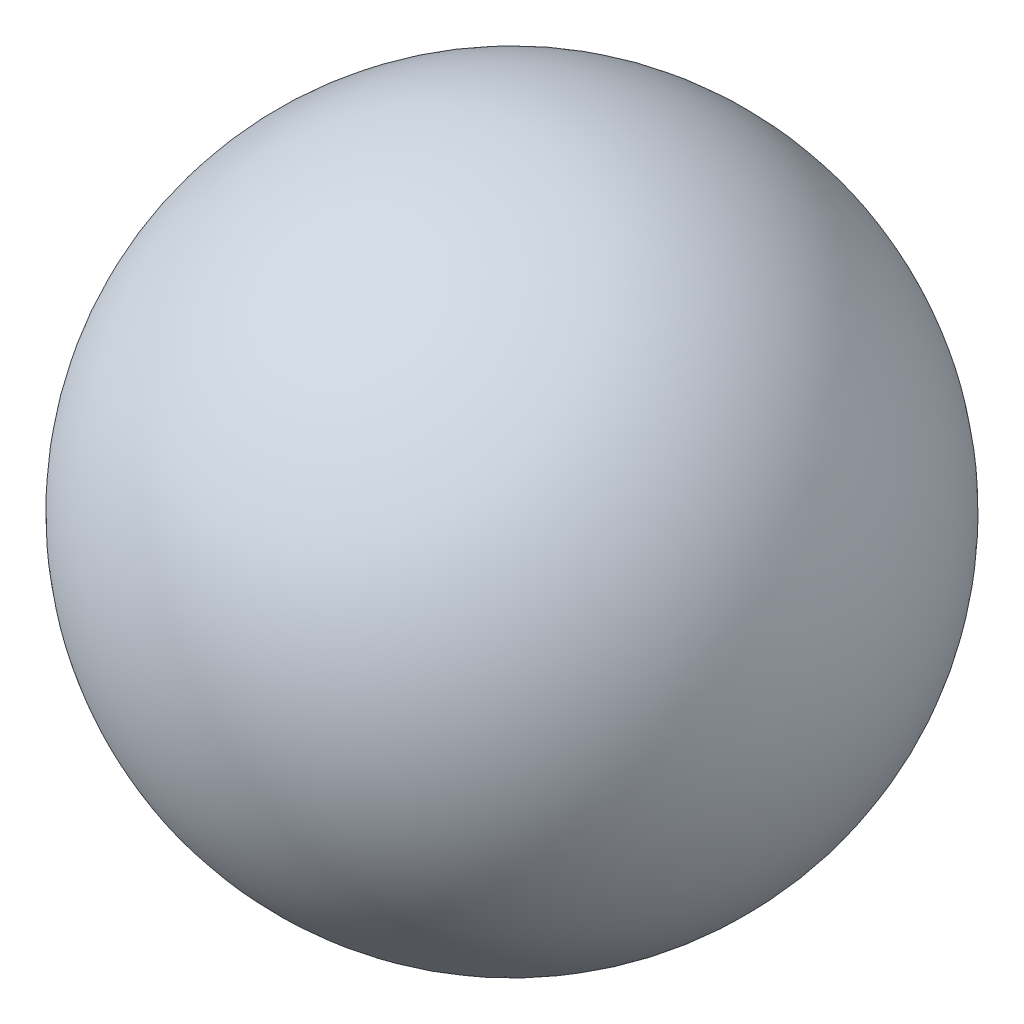
SolidWorks part; units mm, degrees
ref_plane "前基準面" through (0, 0, 0) normal (0, 0, 1) x (1, 0, 0)
ref_plane "上基準面" through (0, 0, 0) normal (0, 1, 0) x (1, 0, 0)
ref_plane "右基準面" through (0, 0, 0) normal (1, 0, 0) x (0, 0, -1)
sketch "草圖1" plane through (0, 0, 0) normal (0, 1, 0) x (1, 0, 0)
  line L0 (0, 30) -> (0, -30)
  arc A0 (0, -30) -> (0, 30) centre (0, 0) ccw
  dimension "D1" = 60
revolve "旋轉1" add sketch "草圖1" angle 360 about L0
